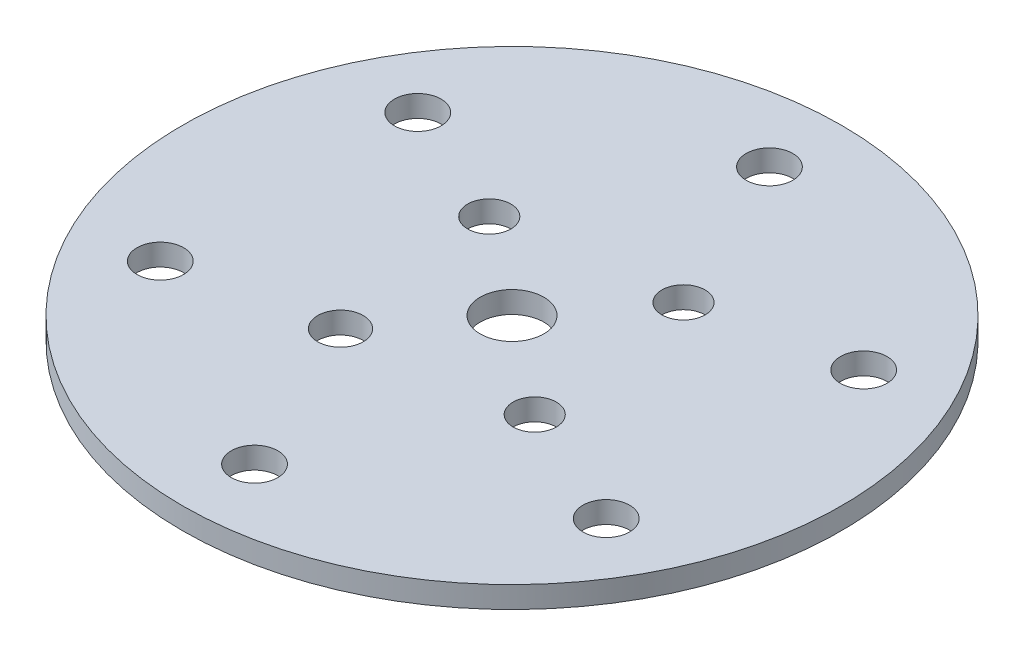
SolidWorks part; units mm, degrees
ref_plane "Front" through (0, 0, 0) normal (0, 0, 1) x (1, 0, 0)
ref_plane "Top" through (0, 0, 0) normal (0, 1, 0) x (1, 0, 0)
ref_plane "Right" through (0, 0, 0) normal (1, 0, 0) x (0, 0, -1)
sketch "Sketch1" plane through (0, 0, 0) normal (0, 1, 0) x (1, 0, 0)
  circle A1 centre (0, 0) radius 30.48
  circle A2 centre (0, -23.8125) radius 2.1526
  circle A3 centre (20.6222, -11.9062) radius 2.1526
  circle A4 centre (20.6222, 11.9063) radius 2.1526
  circle A5 centre (0, 23.8125) radius 2.1526
  circle A6 centre (-20.6222, 11.9062) radius 2.1527
  circle A7 centre (-20.6222, -11.9062) radius 2.1527
  circle A12 centre (0, 0) radius 2.9453
  circle A15 centre (-8.9817, 6.8796) radius 2
  circle A16 centre (6.8796, 8.9817) radius 2
  circle A17 centre (8.9817, -6.8796) radius 2
  circle A18 centre (-6.8796, -8.9817) radius 2.105
extrude "Boss-Extrude1" add sketch "Sketch1" along normal blind 2
